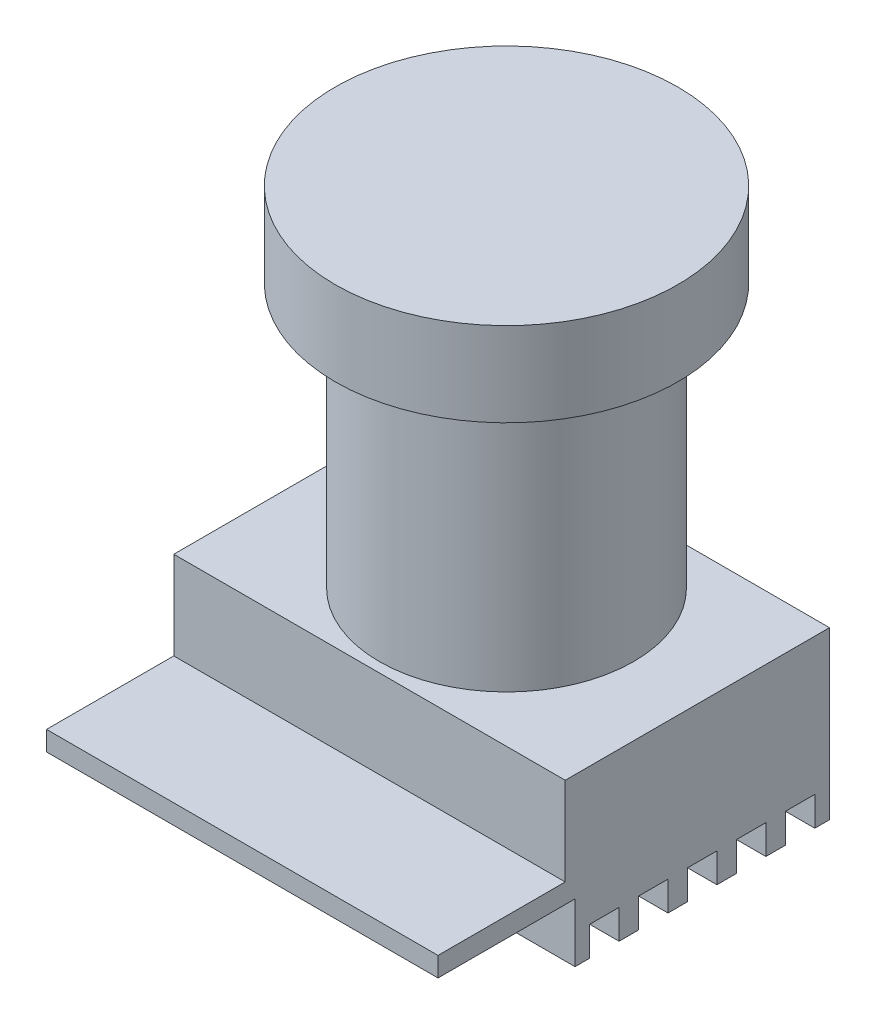
SolidWorks part; units mm, degrees
ref_plane "Front Plane" through (0, 0, 0) normal (0, 0, 1) x (1, 0, 0)
ref_plane "Top Plane" through (0, 0, 0) normal (0, 1, 0) x (1, 0, 0)
ref_plane "Right Plane" through (0, 0, 0) normal (1, 0, 0) x (0, 0, -1)
sketch "Sketch1" plane through (0, 0, 0) normal (0, 1, 0) x (1, 0, 0)
  line L1 (-10, 10) -> (10, 10)
  line L2 (-10, 10) -> (-10, -10)
  line L3 (-10, -10) -> (10, -10)
  line L4 (10, 10) -> (10, -10)
  line L5 (-10, 10) -> (10, -10) construction
  line L6 (-10, -10) -> (10, 10) construction
  point P0 (0, 0)
  dimension "D1" = 20
  dimension "D2" = 20
extrude "PCB" add sketch "Sketch1" along normal blind 1
sketch "Sketch3" plane through (0, 0, 0) normal (0, -1, 0) x (1, 0, 0)
  line L0 (10, 10) -> (10, -10) construction
  line L1 (-10, -10) -> (10, -10)
  line L2 (-10, -10) -> (-10, 3)
  line L3 (-10, 3) -> (10, 3)
  line L4 (10, -10) -> (10, 3)
  dimension "D1" = 13
extrude "HeatSink" add sketch "Sketch3" along normal blind 3
sketch "Sketch4" plane through (-10, 0, 0) normal (-1, 0, 0) x (0, 0, 1)
  line L0 (-3.5, -3) -> (-3.5, 1) construction
  line L1 (3, -3) -> (-10, -3) construction
  line L2 (-10, 1) -> (10, 1) construction
  line L3 (-1.75, -3) -> (-0.25, -3)
  line L4 (-4.25, -3) -> (-2.75, -3)
  line L5 (-4.25, -3) -> (-4.25, -1.5)
  line L6 (-4.25, -1.5) -> (-2.75, -1.5)
  line L7 (-2.75, -3) -> (-2.75, -1.5)
  line L8 (-1.75, -3) -> (-1.75, -1.5)
  line L9 (-1.75, -1.5) -> (-0.25, -1.5)
  line L10 (-0.25, -3) -> (-0.25, -1.5)
  line L11 (0.75, -3) -> (2.25, -3)
  line L12 (0.75, -3) -> (0.75, -1.5)
  line L13 (0.75, -1.5) -> (2.25, -1.5)
  line L14 (2.25, -3) -> (2.25, -1.5)
  line L15 (-6.75, -3) -> (-5.25, -3)
  line L16 (-6.75, -3) -> (-6.75, -1.5)
  line L17 (-6.75, -1.5) -> (-5.25, -1.5)
  line L18 (-5.25, -3) -> (-5.25, -1.5)
  line L19 (-9.25, -3) -> (-7.75, -3)
  line L20 (-9.25, -3) -> (-9.25, -1.5)
  line L21 (-9.25, -1.5) -> (-7.75, -1.5)
  line L22 (-7.75, -3) -> (-7.75, -1.5)
  dimension "D1" = 1.5
  dimension "D2" = 1.5
  dimension "D3" = 3
  dimension "D4" = 3
extrude "HeatSinkPattern" cut sketch "Sketch4" against normal through all
sketch "Sketch5" plane through (0, 1, 0) normal (0, 1, 0) x (1, 0, 0)
  line L0 (10, -10) -> (10, 10) construction
  line L1 (-10, 10) -> (10, 10)
  line L2 (-10, 10) -> (-10, -3.5)
  line L3 (-10, -3.5) -> (10, -3.5)
  line L4 (10, 10) -> (10, -3.5)
  dimension "D1" = 13.5
extrude "CameraBase" add sketch "Sketch5" along normal blind 4.5
sketch "Sketch6" plane through (0, 5.5, 0) normal (0, 1, 0) x (1, 0, 0)
  line L0 (0, 10) -> (0, -3.5) construction
  line L1 (10, 10) -> (-10, 10) construction
  line L2 (-10, -3.5) -> (10, -3.5) construction
  circle A0 centre (0, 3.5) radius 6.5
  dimension "D1" = 6.5
extrude "CameraCylinder" add sketch "Sketch6" along normal blind 13.5
sketch "Sketch7" plane through (0, 19, 0) normal (0, 1, 0) x (1, 0, 0)
  circle A0 centre (0, 3.5) radius 8.75
  dimension "D1" = 17.5
extrude "Lens" add sketch "Sketch7" along normal blind 4.3
